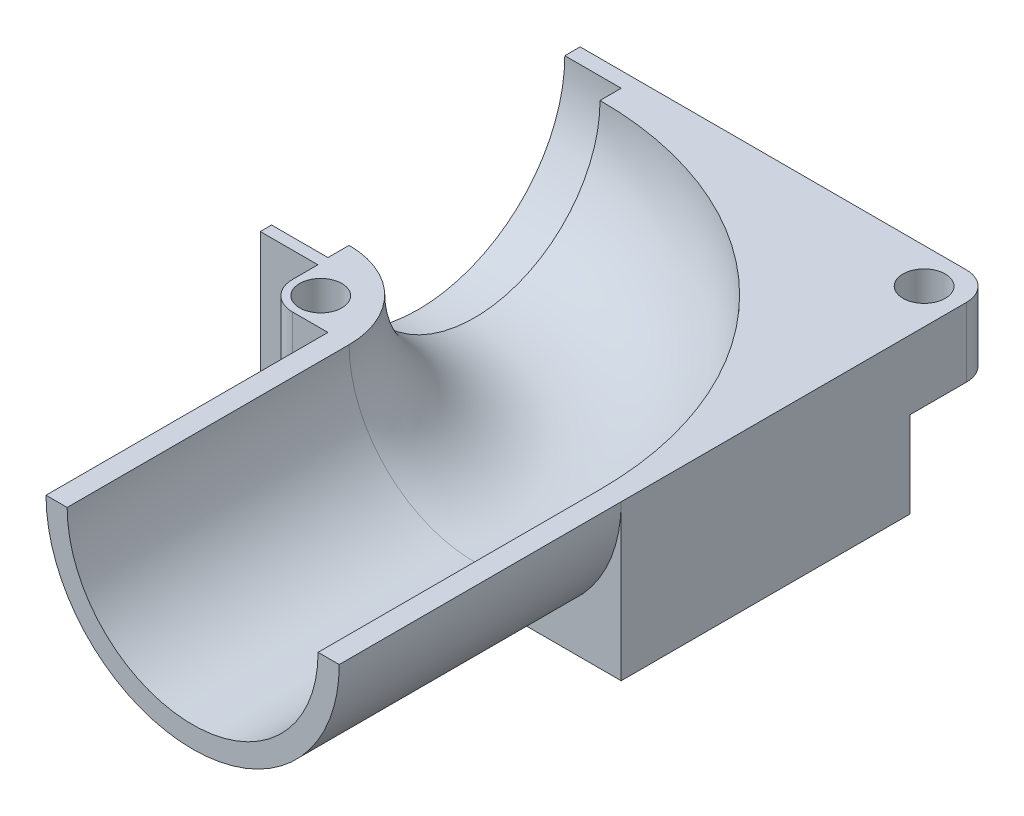
SolidWorks part; units mm, degrees
ref_plane "前视基准面" through (0, 0, 0) normal (0, 0, 1) x (1, 0, 0)
ref_plane "上视基准面" through (0, 0, 0) normal (0, 1, 0) x (1, 0, 0)
ref_plane "右视基准面" through (0, 0, 0) normal (1, 0, 0) x (0, 0, -1)
sketch "草图1" plane through (0, 0, 0) normal (0, 1, 0) x (1, 0, 0)
  line L0 (-35.3121, 0) -> (38.828, 0) construction
  line L1 (0, 20.2293) -> (0, -26.5987) construction
  line L2 (0, 0) -> (4, 0)
  line L3 (19, -15) -> (19, -25)
  arc A0 (4, 0) -> (19, -15) centre (4, -15) cw
  dimension "D2" = 15
  dimension "D1" = 4
  dimension "D3" = 10
sketch "草图2" plane through (0, 0, 0) normal (0, 1, 0) x (1, 0, 0)
  line L0 (0, 20.2293) -> (0, -26.5987) construction
  line L1 (0, 14.4859) -> (31.8391, 14.4859)
  line L2 (0, 14.4859) -> (0, -25)
  line L3 (0, -25) -> (31.8391, -25)
  line L4 (31.8391, 14.4859) -> (31.8391, -25)
extrude "凸台-拉伸1" add sketch "草图2" along normal blind 11
ref_plane "基准面1" through (0, 0, 25) normal (0, 0, 1) x (1, 0, 0)
sketch "草图3" plane through (0, 0, 25) normal (0, 0, 1) x (1, 0, 0)
  line L0 (0, 11) -> (31.8391, 11) construction
  line L1 (10.1, 11) -> (27.9, 11)
  line L2 (19, 0) -> (19, 30.084) construction
  arc A0 (10.1, 11) -> (27.9, 11) centre (19, 11) ccw
sweep "切除-扫描1" cut profiles "草图3" path "草图1"
sketch "草图4" plane through (0, 0, 25) normal (0, 0, 1) x (1, 0, 0)
  line L0 (0, 11) -> (10.1, 11) construction
  line L1 (-2.1091, 11) -> (8.6, 11)
  line L2 (-2.1091, 11) -> (-2.1091, -3.5775)
  line L3 (-2.1091, -3.5775) -> (35.025, -3.5775)
  line L4 (35.025, 11) -> (35.025, -3.5775)
  line L5 (29.4, 11) -> (35.025, 11)
  arc A0 (8.6, 11) -> (29.4, 11) centre (19, 11) ccw
  arc A1 (10.1, 11) -> (27.9, 11) centre (19, 11) ccw construction
extrude "切除-拉伸1" cut sketch "草图4" against normal blind 10
sketch "草图5" plane through (0, 0, 0) normal (1, 0, 0) x (0, 0, -1)
  line L0 (18.0538, 11) -> (-27.2482, 11) construction
  line L1 (14.4859, 11) -> (8.9, 11) construction
  line L2 (10.4, 11) -> (-10.4, 11)
  arc A0 (10.4, 11) -> (-10.4, 11) centre (0, 11) cw
  arc A1 (-8.9, 11) -> (8.9, 11) centre (0, 11) ccw construction
extrude "切除-拉伸2" cut sketch "草图5" along normal blind 4
sketch "草图6" plane through (0, 0, 0) normal (0, 1, 0) x (1, 0, 0)
  line L0 (29.4, -15) -> (31.8391, -15)
  line L1 (31.8391, -15) -> (31.8391, 14.4859)
  line L2 (31.8391, 14.4859) -> (0, 14.4859)
  line L3 (0, 14.4859) -> (0, 11.4859)
  line L4 (0, 14.4859) -> (0, 10.4) construction
  line L5 (0, 11.4859) -> (27.4, 11.4859)
  line L6 (29.4, 9.4859) -> (29.4, -15)
  line L8 (0, -11.2) -> (4.0874, -11.2)
  line L9 (0, 14.4859) -> (0, -15) construction
  line L10 (4.0874, -11.2) -> (4.0874, -13)
  line L12 (6.0874, -15) -> (0, -15)
  line L13 (0, -15) -> (0, -11.2)
  arc A0 (27.4, 11.4859) -> (29.4, 9.4859) centre (27.4, 9.4859) cw
  arc A1 (6.0874, -15) -> (4.0874, -13) centre (6.0874, -13) cw
  point P21 (2.0437, -11.2)
  dimension "D1" = 2
  dimension "D2" = 2
  dimension "D3" = 3
  dimension "D4" = 3.8
  dimension "D5" = 22.6859
extrude "切除-拉伸3" cut sketch "草图6" along normal through all
sketch "草图7" plane through (0, 0, 0) normal (0, 1, 0) x (1, 0, 0)
  line L0 (4.0874, -10.7082) -> (4.0874, -13)
  line L1 (8.6, -15) -> (6.0874, -15)
  line L2 (4.0874, -10.7082) -> (6.6, -10.7082)
  line L3 (8.6, -12.7082) -> (8.6, -15)
  line L4 (23.4, 11.4859) -> (27.4, 11.4859)
  line L5 (29.4, 5.4859) -> (29.4, 9.4859)
  line L6 (29.4, 9.4859) -> (29.4, -15) construction
  line L7 (23.4, 11.4859) -> (23.4, 7.4859)
  line L8 (25.4, 5.4859) -> (29.4, 5.4859)
  line L9 (0, 11.4859) -> (27.4, 11.4859) construction
  line L10 (4.0874, -13) -> (4.0874, -11.2) construction
  arc A0 (6.6, -10.7082) -> (8.6, -12.7082) centre (6.6, -12.7082) cw
  arc A1 (4.0874, -13) -> (6.0874, -15) centre (6.0874, -13) ccw
  arc A2 (23.4, 7.4859) -> (25.4, 5.4859) centre (25.4, 7.4859) ccw
  arc A3 (29.4, 9.4859) -> (27.4, 11.4859) centre (27.4, 9.4859) ccw
  dimension "D1" = 2
  dimension "D2" = 2
  dimension "D3" = 2
  dimension "D4" = 2
  dimension "D5" = 4
  dimension "D6" = 4
extrude "切除-拉伸4" cut sketch "草图7" along normal blind 6.1
sketch "草图8" plane through (0, 0, 0) normal (0, 1, 0) x (1, 0, 0)
  line L0 (4.0874, -13) -> (4.0874, -11.2) construction
  line L1 (8.6, -15) -> (6.0874, -15) construction
  line L2 (29.4, 9.4859) -> (29.4, -15) construction
  line L3 (0, 11.4859) -> (27.4, 11.4859) construction
  circle A0 centre (6.0874, -13) radius 1.5
  circle A1 centre (26.9, 8.9859) radius 1.5
  dimension "D1" = 2
  dimension "D2" = 2
  dimension "D3" = 2.5
  dimension "D4" = 2.5
extrude "切除-拉伸5" cut sketch "草图8" along normal through all
cosmetic thread "装饰螺纹线1" parameters "D2"=9
cosmetic thread "装饰螺纹线2" parameters "D2"=9
ref_plane "基准面2" through (-10, 0, 0) normal (-1, 0, 0) x (0, 0, 1)
sketch "草图9" plane through (0, 0, 25) normal (0, 0, 1) x (1, 0, 0)
  line L0 (-4.6594, 11) -> (42.3878, 11) construction
  line L1 (27.9, 11) -> (29.4, 11) construction
  line L2 (27.9, 11) -> (29.4, 11)
  line L3 (10.1, 11) -> (8.6, 11)
  arc A0 (10.1, 11) -> (27.9, 11) centre (19, 11) ccw
  arc A1 (8.6, 11) -> (29.4, 11) centre (19, 11) ccw
  arc A2 (10.1, 11) -> (27.9, 11) centre (19, 11) ccw construction
  arc A3 (8.6, 11) -> (29.4, 11) centre (19, 11) ccw construction
extrude "凸台-拉伸2" add sketch "草图9" along normal blind 10
